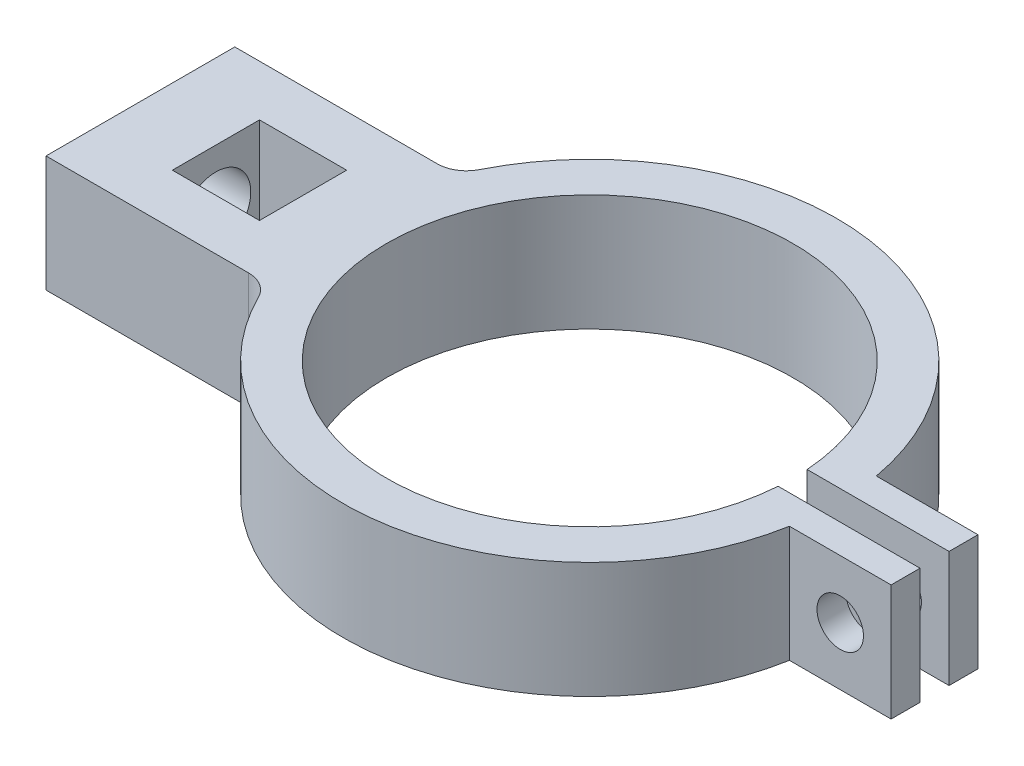
SolidWorks part; units mm, degrees
ref_plane "Front Plane" through (0, 0, 0) normal (0, 0, 1) x (1, 0, 0)
ref_plane "Top Plane" through (0, 0, 0) normal (0, 1, 0) x (1, 0, 0)
ref_plane "Right Plane" through (0, 0, 0) normal (1, 0, 0) x (0, 0, -1)
sketch "Sketch1" plane through (0, 0, 0) normal (0, 1, 0) x (1, 0, 0)
  line L1 (30.1412, 3.8096) -> (30.1412, 1.2787)
  line L3 (21.2512, 3.8096) -> (30.1412, 3.8096)
  line L6 (21.2543, -3.7923) -> (30.1443, -3.7923)
  line L16 (-39.292, 8.255) -> (-39.292, -8.255)
  line L17 (-19.9495, 8.255) -> (-39.292, 8.255)
  line L18 (-19.9495, -8.255) -> (-39.292, -8.255)
  line L19 (30.1443, -1.2613) -> (17.7328, -1.2613)
  line L20 (30.1412, 1.2787) -> (17.7315, 1.2787)
  line L22 (-32.688, -3.8104) -> (-25.068, -3.8104)
  line L23 (-32.688, -3.8104) -> (-32.688, 3.8096)
  line L24 (-32.688, 3.8096) -> (-25.068, 3.8096)
  line L25 (30.1443, -1.2613) -> (30.1443, -3.7923)
  line L26 (-25.068, -3.8104) -> (-25.068, 3.8096)
  line L27 (-32.688, -3.8104) -> (-25.068, 3.8096) construction
  line L28 (-32.688, 3.8096) -> (-25.068, -3.8104) construction
  arc A5 (17.7315, 1.2787) -> (17.7328, -1.2613) centre (0, 0) ccw
  arc A6 (21.2512, 3.8096) -> (-19.9495, 8.255) centre (0, 0) ccw
  arc A7 (-19.9495, -8.255) -> (21.2543, -3.7923) centre (0, 0) ccw
  point P0 (-28.878, -0.0004)
  dimension "D1" = 6.604
extrude "Boss-Extrude3" add sketch "Sketch1" along normal blind 10.16
sketch "Sketch5" plane through (0, 0, -3.8096) normal (0, 0, -1) x (-1, 0, 0)
  circle A0 centre (-25.6962, 5.08) radius 2.032
  dimension "D1" = 4.064
extrude "Cut-Extrude1" cut sketch "Sketch5" against normal up to surface (7.6019 mm away) up to face at (25.6993, 5.08, 3.7923)
sketch "Sketch6" plane through (-39.292, 0, 0) normal (-1, 0, 0) x (0, 0, 1)
  circle A0 centre (0, 5.08) radius 3.048
  dimension "D1" = 6.096
extrude "Cut-Extrude2" cut sketch "Sketch6" against normal up to surface (6.604 mm away) up to face at (-32.688, 5.08, 0.0004)
fillet "Fillet1" radius 2.54 2 edges at (-19.9495, 5.08, -8.255) (-19.9495, 5.08, 8.255)
